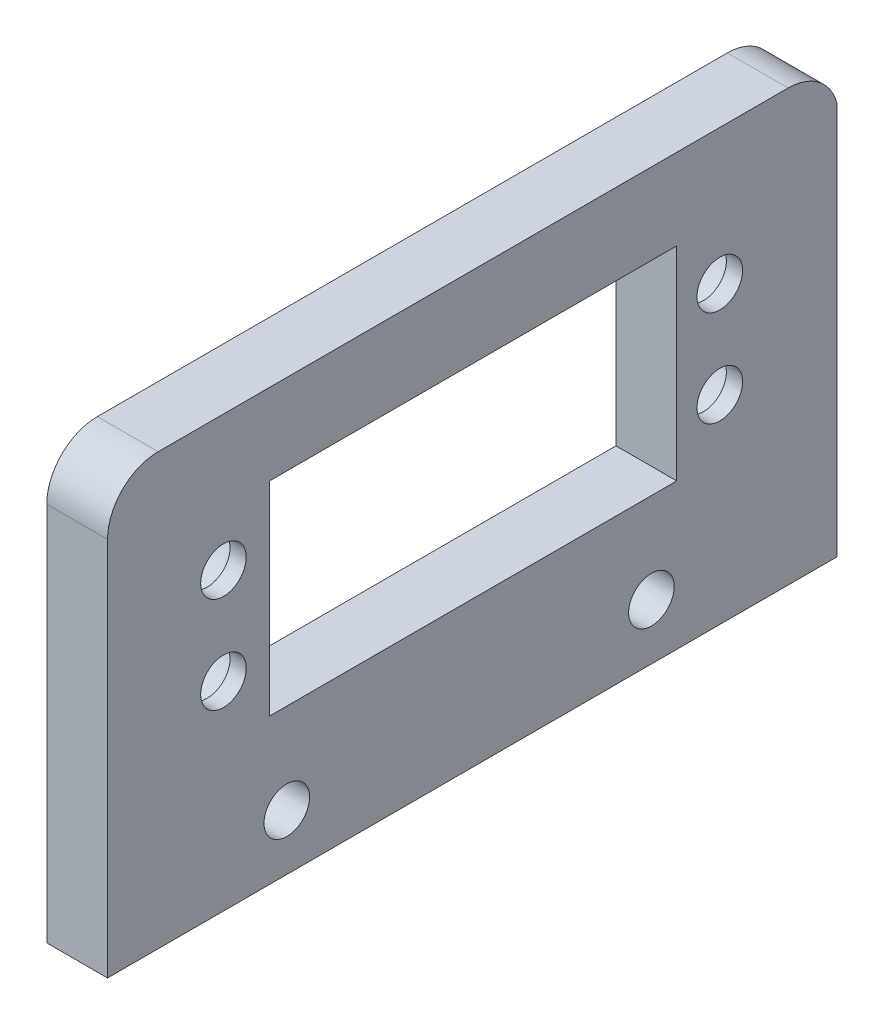
SolidWorks part; units mm, degrees
ref_plane "Front Plane" through (0, 0, 0) normal (0, 0, 1) x (1, 0, 0)
ref_plane "Top Plane" through (0, 0, 0) normal (0, 1, 0) x (1, 0, 0)
ref_plane "Right Plane" through (0, 0, 0) normal (1, 0, 0) x (0, 0, -1)
sketch "Sketch1" plane through (0, 0, 0) normal (1, 0, 0) x (0, 0, -1)
  line L0 (-36.0961, -19.95) -> (-36.0961, 17.55)
  line L1 (-31.0961, 22.55) -> (31.0961, 22.55)
  line L2 (35.9468, 18.7627) -> (35.9468, -19.95)
  line L3 (35.9468, -19.95) -> (-36.0961, -19.95)
  line L4 (0, 22.55) -> (0, 4.5) construction
  line L5 (20.1, -5.55) -> (-20.1, -5.55)
  line L6 (20.1, -5.55) -> (20.1, 14.55)
  line L7 (20.1, 14.55) -> (-20.1, 14.55)
  line L8 (-20.1, -5.55) -> (-20.1, 14.55)
  line L9 (20.1, -5.55) -> (-20.1, 14.55) construction
  line L10 (20.1, 14.55) -> (-20.1, -5.55) construction
  arc A0 (31.0961, 22.55) -> (35.9468, 18.7627) centre (31.0961, 17.55) cw
  arc A1 (-36.0961, 17.55) -> (-31.0961, 22.55) centre (-31.0961, 17.55) cw
  point P5 (0, 4.5)
  dimension "D7" = 5
  dimension "D1" = 20.1
  dimension "D2" = 8
  dimension "D3" = 42.5
  dimension "D8" = 20.1
  dimension "D9" = 31.0961
  dimension "D10" = 35.9468
  dimension "D11" = 4.5
extrude "Boss-Extrude1" add sketch "Sketch1" along normal blind 6 contours L8 L5 L6 L7 | L1 A0 L2 L3 L0 A1
hole_wizard "CBORE for M4 Hex Socket Head Cap Screw1" positions "Sketch2" profile "Sketch3" counterbore size "M4" standard "DIN" end condition through all
sketch "Sketch2" plane through (0, -170.7125, -177.83) normal (-1, 0, 0) x (0, 0, 1)
  point P0 (202.48, 170.4125)
  point P1 (202.48, 179.9125)
  point P2 (153.48, 170.4125)
  point P3 (153.48, 179.9125)
sketch "Sketch3" plane through (0, -0.3, 24.65) normal (0, 1, 0) x (0, 0, 1)
  line L0 (0, 0) -> (0, 6)
  line L1 (0, 6) -> (2.25, 6)
  line L2 (2.25, 6) -> (2.25, 4.4)
  line L3 (2.25, 4.4) -> (4, 4.4)
  line L4 (4, 4.4) -> (4, 0)
  line L5 (4, 0) -> (0, 0)
  line L6 (0, -6.35) -> (0, 107.95) construction
  dimension "Thru Hole Dia." = 4.5
  dimension "Thru Hole Depth" = 6
  dimension "C'Bore Dia." = 8
  dimension "C'Bore Depth" = 4.4
hole_wizard "M4 Clearance Hole1" positions "Sketch4" profile "Sketch5" hole size "M4" standard "DIN" end condition through all
sketch "Sketch4" plane through (0, -170.7125, -177.83) normal (-1, 0, 0) x (0, 0, 1)
  line L0 (148.23, 156.2625) -> (208.23, 156.2625) construction
  point P9 (160.23, 156.2625)
  point P11 (196.23, 156.2625)
sketch "Sketch5" plane through (0, -14.45, -17.6) normal (0, 1, 0) x (0, 0, 1)
  line L0 (0, 0) -> (0, 6)
  line L1 (0, 6) -> (2.25, 6)
  line L2 (2.25, 6) -> (2.25, 0)
  line L3 (2.25, 0) -> (0, 0)
  line L4 (0, -6.35) -> (0, 107.95) construction
  dimension "Thru Hole Dia." = 4.5
  dimension "Thru Hole Depth" = 6
